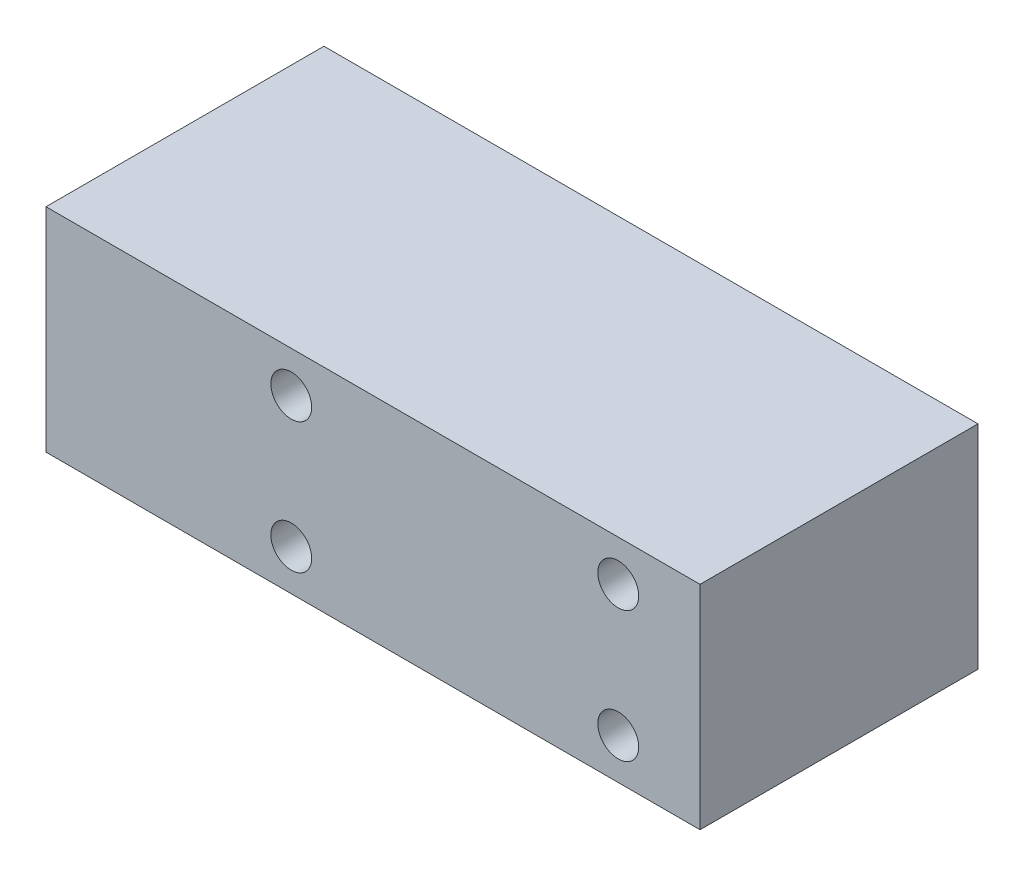
SolidWorks part; units mm, degrees
material "铝材"
ref_plane "前基準面" through (0, 0, 0) normal (0, 0, 1) x (1, 0, 0)
ref_plane "上基準面" through (0, 0, 0) normal (0, 1, 0) x (1, 0, 0)
ref_plane "右基準面" through (0, 0, 0) normal (1, 0, 0) x (0, 0, -1)
sketch "草图1" plane through (0, 0, 0) normal (0, 0, 1) x (1, 0, 0)
  line L1 (0, 0) -> (80, 0)
  line L2 (0, 0) -> (0, 26)
  line L3 (0, 26) -> (80, 26)
  line L4 (80, 0) -> (80, 26)
  dimension "D1" = 80
  dimension "D2" = 26
extrude "凸台-拉伸1" add sketch "草图1" along normal blind 34
hole_wizard "M6 螺纹孔1" positions "草图3" profile "草图2" tap size "M6" standard "ISO"
sketch "草图3" plane through (0, 0, 34) normal (0, 0, 1) x (1, 0, 0)
  line L0 (0, 13) -> (80, 13) construction
  line L1 (0, 26) -> (0, 0) construction
  line L2 (80, 0) -> (80, 26) construction
  point P0 (70, 21)
  point P14 (70, 5)
  point P17 (30, 21)
  point P19 (30, 5)
  dimension "D1" = 16
  dimension "D2" = 30
  dimension "D4" = 40
sketch "草图2" plane through (70, 21, 34) normal (1, 0, 0) x (0, -1, 0)
  line L0 (0, 0) -> (0, 16.5022)
  line L1 (0, 16.5022) -> (2.5, 15)
  line L2 (2.5, 15) -> (2.5, 0)
  line L5 (2.5, 0) -> (0, 0)
  line L10 (0, 16.5022) -> (-2.5, 15) construction
  line L11 (0, -6.35) -> (0, 107.95) construction
  dimension "螺纹孔钻头直径" = 5
  dimension "螺纹孔钻头深度" = 15
  dimension "导头角度" = 118
cosmetic thread "孔螺蚊线1" parameters "D1"=12, "D2"=6
cosmetic thread "孔螺蚊线2" parameters "D1"=12, "D2"=6
cosmetic thread "孔螺蚊线3" parameters "D1"=12, "D2"=6
cosmetic thread "孔螺蚊线4" parameters "D1"=12, "D2"=6
hole_wizard "M6 螺纹孔2" positions "草图5" profile "草图4" tap size "M6" standard "ISO"
sketch "草图5" plane through (0, 0, 0) normal (0, 0, -1) x (-1, 0, 0)
  line L0 (-80, 13) -> (0, 13) construction
  line L1 (-80, 0) -> (-80, 26) construction
  line L2 (0, 26) -> (0, 0) construction
  point P0 (-10, 5)
  point P1 (-10, 21)
  point P3 (-70, 21)
  point P5 (-70, 5)
  dimension "D1" = 16
  dimension "D2" = 10
  dimension "D3" = 60
sketch "草图4" plane through (10, 5, 0) normal (1, 0, 0) x (0, 1, 0)
  line L0 (0, 0) -> (0, 16.5022)
  line L1 (0, 16.5022) -> (2.5, 15)
  line L2 (2.5, 15) -> (2.5, 0)
  line L5 (2.5, 0) -> (0, 0)
  line L10 (0, 16.5022) -> (-2.5, 15) construction
  line L11 (0, -6.35) -> (0, 107.95) construction
  dimension "螺纹孔钻头直径" = 5
  dimension "螺纹孔钻头深度" = 15
  dimension "导头角度" = 118
cosmetic thread "孔螺蚊线5" parameters "D1"=12, "D2"=6
cosmetic thread "孔螺蚊线6" parameters "D1"=12, "D2"=6
cosmetic thread "孔螺蚊线7" parameters "D1"=12, "D2"=6
cosmetic thread "孔螺蚊线8" parameters "D1"=12, "D2"=6
